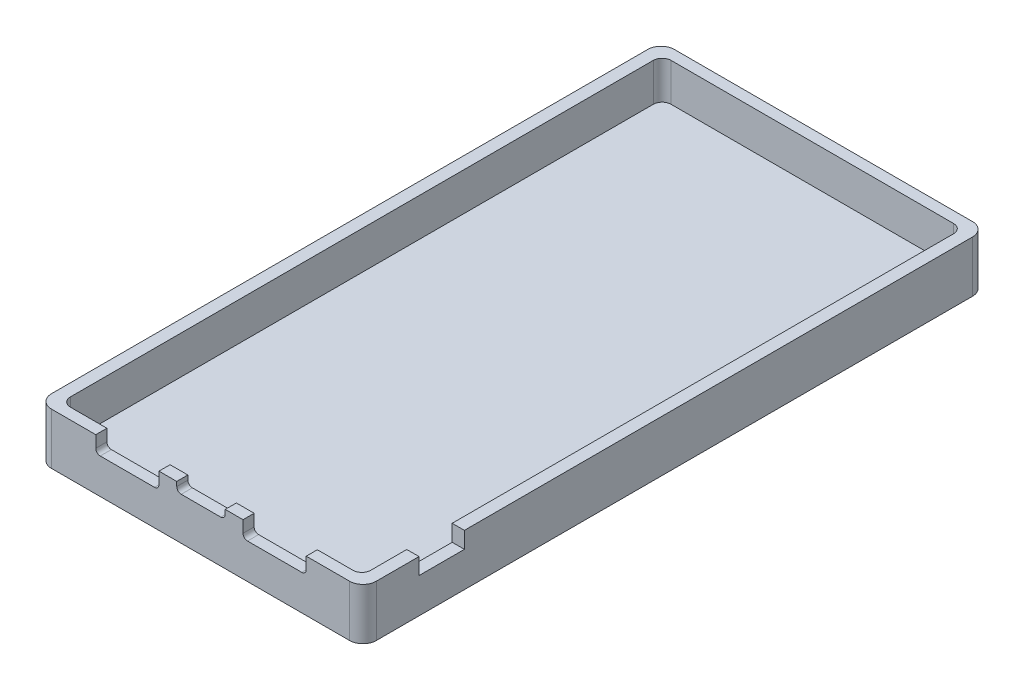
SolidWorks part; units mm, degrees
ref_plane "Front Plane" through (0, 0, 0) normal (0, 0, 1) x (1, 0, 0)
ref_plane "Top Plane" through (0, 0, 0) normal (0, 1, 0) x (1, 0, 0)
ref_plane "Right Plane" through (0, 0, 0) normal (1, 0, 0) x (0, 0, -1)
sketch "Sketch1" plane through (0, 0, 0) normal (0, 1, 0) x (1, 0, 0)
  line L0 (0, 0) -> (73, 0)
  line L1 (73, 0) -> (73, 140)
  line L2 (73, 140) -> (0, 140)
  line L3 (0, 140) -> (0, 0)
  dimension "D1" = 73
  dimension "D2" = 140
extrude "Boss-Extrude1" add sketch "Sketch1" along normal blind 16
sketch "Sketch2" plane through (0, 16, 0) normal (0, 1, 0) x (1, 0, 0)
  line L0 (2.75, 137.5) -> (70.25, 137.5)
  line L1 (70.25, 137.5) -> (70.25, 2.5)
  line L2 (70.25, 2.5) -> (2.75, 2.5)
  line L3 (2.75, 2.5) -> (2.75, 137.5)
  line L4 (0, 88.4501) -> (2.75, 88.4501) construction
  line L5 (0, 140) -> (0, 0) construction
  line L6 (70.25, 95.5468) -> (73, 95.5468) construction
  line L7 (73, 0) -> (73, 140) construction
  line L8 (27.5525, 0) -> (27.5525, 2.5) construction
  line L9 (0, 0) -> (73, 0) construction
  line L10 (36.5, 137.5) -> (36.5, 140) construction
  line L11 (73, 140) -> (0, 140) construction
  dimension "D1" = 135
  dimension "D2" = 67.5
extrude "Cut-Extrude1" cut sketch "Sketch2" against normal blind 13
sketch "Sketch3" plane through (0, 0, 0) normal (0, 0, 1) x (1, 0, 0)
  line L0 (13.95, 13.35) -> (13.95, 8.9) construction
  line L1 (13.95, 8.9) -> (26.15, 8.9) construction
  line L2 (26.15, 8.9) -> (26.15, 13.35) construction
  line L3 (26.15, 13.35) -> (13.95, 13.35) construction
  line L4 (32.15, 13.35) -> (41.05, 13.35) construction
  line L5 (32.15, 10.55) -> (41.05, 10.55) construction
  line L6 (32.15, 13.35) -> (32.15, 10.55) construction
  line L7 (32.15, 12.35) -> (32.15, 11.55) construction
  line L8 (41.05, 13.35) -> (41.05, 10.55) construction
  line L9 (41.05, 11.55) -> (41.05, 12.35) construction
  line L10 (47.05, 13.35) -> (59.25, 13.35) construction
  line L11 (59.25, 13.35) -> (59.25, 8.9) construction
  line L12 (59.25, 8.9) -> (47.05, 8.9) construction
  line L13 (47.05, 8.9) -> (47.05, 13.35) construction
  line L14 (27.15, 14.35) -> (12.95, 14.35)
  line L15 (12.95, 14.35) -> (12.95, 7.9)
  line L16 (12.95, 7.9) -> (27.15, 7.9)
  line L17 (27.15, 7.9) -> (27.15, 14.35)
  line L18 (31.15, 9.55) -> (42.05, 9.55)
  line L19 (42.05, 14.35) -> (42.05, 9.55)
  line L20 (31.15, 14.35) -> (42.05, 14.35)
  line L21 (31.15, 14.35) -> (31.15, 9.55)
  line L22 (46.05, 7.9) -> (46.05, 14.35)
  line L23 (46.05, 14.35) -> (60.25, 14.35)
  line L24 (60.25, 14.35) -> (60.25, 7.9)
  line L25 (60.25, 7.9) -> (46.05, 7.9)
  dimension "D1" = 1
  dimension "D2" = 1
  dimension "D3" = 1
extrude "Cut-Extrude2" cut sketch "Sketch3" against normal up to surface (2.5 mm away) up to face at (36.5, 9.5, -2.5)
fillet "Fillet1" radius 3 4 edges at (0, 8, -140) (73, 8, -140) (73, 8, 0) (0, 8, 0)
sketch "Sketch4" plane through (73, 0, 0) normal (1, 0, 0) x (0, 0, -1)
  line L0 (13.6, 12.35) -> (21.8, 12.35) construction
  line L1 (21.8, 12.35) -> (21.8, 8.85) construction
  line L2 (21.8, 8.85) -> (13.6, 8.85) construction
  line L3 (13.6, 8.85) -> (13.6, 12.35) construction
  line L4 (12.6, 7.85) -> (12.6, 13.35)
  line L5 (12.6, 13.35) -> (22.8, 13.35)
  line L6 (22.8, 13.35) -> (22.8, 7.85)
  line L7 (22.8, 7.85) -> (12.6, 7.85)
  dimension "D1" = 1
extrude "Cut-Extrude3" cut sketch "Sketch4" against normal up to surface (2.75 mm away) up to face at (70.25, 9.5, -70)
sketch "Sketch5" plane through (70.25, 0, 0) normal (-1, 0, 0) x (0, 0, 1)
  line L0 (-21.8, 12.35) -> (-13.6, 12.35)
  line L1 (-13.6, 12.35) -> (-13.6, 8.85)
  line L2 (-13.6, 8.85) -> (-21.8, 8.85)
  line L3 (-21.8, 8.85) -> (-21.8, 12.35)
fillet "Fillet2" radius 1 12 edges at (46.05, 14.35, -1.25) (60.25, 14.35, -1.25) (60.25, 7.9, -1.25) (46.05, 7.9, -1.25) (31.15, 14.35, -1.25) (42.05, 9.55, -1.25) (42.05, 14.35, -1.25) (31.15, 9.55, -1.25) (12.95, 14.35, -1.25) (27.15, 14.35, -1.25) (27.15, 7.9, -1.25) (12.95, 7.9, -1.25)
fillet "Fillet3" radius 1 8 edges at (0.8787, 16, -139.1213) (36.5, 16, -140) (72.1213, 16, -139.1213) (73, 16, -70) (72.1213, 16, -0.8787) (36.5, 16, 0) (0.8787, 16, -0.8787) (0, 16, -70)
fillet "Fillet4" radius 2 4 edges at (70.25, 9.5, -2.5) (70.25, 9.5, -137.5) (2.75, 9.5, -137.5) (2.75, 9.5, -2.5)
chamfer "Chamfer1" distance 1 angle 45 8 edges at (36.5, 16, -137.5) (70.25, 16, -70) (36.5, 16, -2.5) (2.75, 16, -70) (69.6642, 16, -136.9142) (69.6642, 16, -3.0858) (3.3358, 16, -136.9142) (3.3358, 16, -3.0858)
sketch "Sketch6" plane through (0, 0, 0) normal (0, 0, 1) x (1, 0, 0)
  line L0 (32.15, 9.55) -> (41.05, 9.55) construction
  line L1 (-10.7785, 11.55) -> (81.4185, 11.55)
  line L2 (-10.7785, 11.55) -> (-10.7785, 30.1152)
  line L3 (-10.7785, 30.1152) -> (81.4185, 30.1152)
  line L4 (81.4185, 11.55) -> (81.4185, 30.1152)
  dimension "D1" = 2
extrude "Cut-Extrude4" cut sketch "Sketch6" against normal through all
